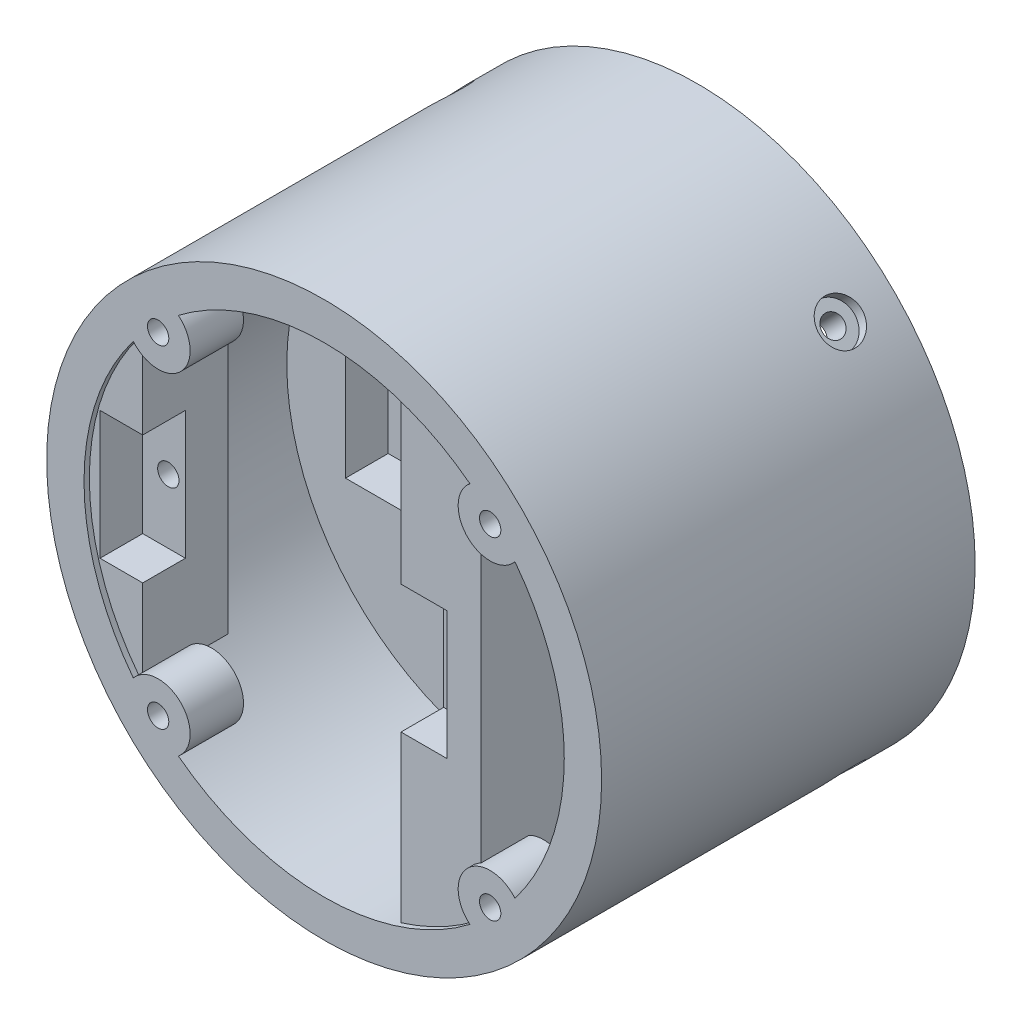
SolidWorks part; units mm, degrees
material "ABS"
ref_plane "Спереди" through (0, 0, 0) normal (0, 0, 1) x (1, 0, 0)
ref_plane "Сверху" through (0, 0, 0) normal (0, 1, 0) x (1, 0, 0)
ref_plane "Справа" through (0, 0, 0) normal (1, 0, 0) x (0, 0, -1)
sketch "Эскиз1" plane through (0, 0, 0) normal (0, 0, 1) x (1, 0, 0)
  circle A1 centre (0, 0) radius 26
  dimension "D1" = 52
extrude "Бобышка-Вытянуть1" add sketch "Эскиз1" along normal blind 35
sketch "Эскиз3" plane through (0, 0, 0) normal (0, 0, -1) x (-1, 0, 0)
  circle A0 centre (0, 0) radius 22.5
  dimension "D1" = 45
extrude "Вырез-Вытянуть1" cut sketch "Эскиз3" against normal blind 11 contours A0
sketch "Эскиз10" plane through (0, 0, 11) normal (0, 0, -1) x (-1, 0, 0)
  circle A0 centre (0, 0) radius 15
  dimension "D1" = 30
sketch "Эскиз4" plane through (0, 0, 35) normal (0, 0, 1) x (1, 0, 0)
  circle A0 centre (0, 0) radius 22.5
  dimension "D1" = 45
extrude "Вырез-Вытянуть2" cut sketch "Эскиз4" against normal offset from surface (19 mm away) 5 up to face at (-22.5, 0, 11)
sketch "Эскиз13" plane through (0, 0, 16) normal (0, 0, 1) x (1, 0, 0)
  line L0 (0, 26) -> (0, -26) construction
  line L1 (-26, 0) -> (26, 0) construction
  line L3 (-17, 6.5) -> (7, 6.5)
  line L4 (-17, 6.5) -> (-17, -6.5)
  line L5 (-17, -6.5) -> (7, -6.5)
  line L6 (7, 6.5) -> (7, -6.5)
  circle A0 centre (0, 0) radius 26 construction
  point P11 (-17, 0)
  point P13 (-5, 6.5)
  dimension "D1" = 13
  dimension "D2" = 24
  dimension "D3" = 5
extrude "Вырез-Вытянуть3" cut sketch "Эскиз13" against normal blind 4
sketch "Эскиз12" plane through (0, 0, 35) normal (0, 0, 1) x (1, 0, 0)
  line L0 (0, 26) -> (0, -26) construction
  line L1 (0, 0) -> (28.1458, 16.25) construction
  line L2 (-26, 0) -> (32.5, 0) construction
  line L5 (19.4856, 11.25) -> (22.5167, 13)
  line L6 (19.4856, -11.25) -> (22.5167, -13)
  circle A0 centre (0, 0) radius 26 construction
  arc A4 (19.4856, -11.25) -> (19.4856, 11.25) centre (0, 0) ccw
  arc A6 (22.5167, -13) -> (22.5167, 13) centre (0, 0) ccw
  dimension "D1" = 30
ref_plane "Плоскость2" through (0, 0, 26.5) normal (0, 0, 1) x (1, 0, 0)
sketch "Эскиз14" plane through (0, 0, 26.5) normal (0, 0, 1) x (1, 0, 0)
  line L1 (7, 0) -> (-46.5151, 0) construction
  line L2 (7, -6.5) -> (7, 6.5) construction
  line L3 (-17.5, -28.5313) -> (-17.5, 17.8536) construction
  line L6 (7, 0) -> (57.6607, 0) construction
  line L8 (14.2, -44.5711) -> (14.2, 20) construction
  line L10 (14.2, -20.5757) -> (14.2, 20.5757)
  line L13 (-17.5, -17.8536) -> (-17.5, 17.8536)
  line L15 (6.7, -24.0855) -> (6.7, 24.0855)
  line L16 (0, -28.5313) -> (0, 28.5313) construction
  arc A4 (-17.5, 17.8536) -> (-17.5, -17.8536) centre (0, 0) ccw
  arc A5 (14.2, 20.5757) -> (6.7, 24.0855) centre (0, 0) ccw
  arc A6 (6.7, -24.0855) -> (14.2, -20.5757) centre (0, 0) ccw
  point P11 (-17.5, 0)
  point P18 (7, 0)
  point P22 (14.2, 0)
  point P27 (14.2, 0)
  point P29 (-17.5, 0)
  point P33 (7.5, 0)
  point P34 (6.7, 0)
  point P35 (0, 0)
  dimension "D1" = 17.5
  dimension "D4" = 6.7
extrude "Бобышка-Вытянуть2" add sketch "Эскиз14" along normal blind 8
sketch "Эскиз15" plane through (0, 0, 34.5) normal (0, 0, 1) x (1, 0, 0)
  line L0 (43.3889, 0) -> (-43.3889, 0) construction
  line L1 (0, 36.1435) -> (0, -36.1435) construction
  line L2 (-21.5, 29.8665) -> (-21.5, -29.8665) construction
  line L3 (11, 32.0712) -> (11, -32.0712) construction
  line L4 (-17.5, 23.7559) -> (-17.5, -23.2484) construction
  line L5 (-21.5, -6) -> (-21.5, 6)
  line L6 (-21.5, 6) -> (-17.5, 6)
  line L7 (6.7, 41.39) -> (6.7, -19.4927) construction
  line L8 (6.7, 21.4793) -> (6.7, -21.4793) construction
  line L9 (11, -6) -> (11, 6)
  line L10 (11, 6) -> (6.7, 6)
  line L11 (-17.5, 6) -> (-17.5, -6)
  line L12 (6.7, 6) -> (6.7, -6)
  line L13 (11, -6) -> (6.7, -6)
  line L14 (-21.5, -6) -> (-17.5, -6)
  point P4 (0, 0)
  point P8 (0, 0)
  point P11 (-21.5, 0)
  point P14 (11, 0)
  point P19 (-17.5, 0.2537)
  point P24 (6.7, 10.9487)
  point P30 (6.7, 0)
  point P31 (11, 0)
  point P32 (-17.5, 0)
  point P33 (-21.5, 0)
  dimension "D1" = 21.5
  dimension "D2" = 11
  dimension "D3" = 6
  dimension "D4" = 6
extrude "Вырез-Вытянуть5" cut sketch "Эскиз15" along direction (0, 0, 1) on the side against the normal offset from surface (4 mm away) 18.5
sketch "Эскиз17" plane through (0, 0, 30.5) normal (0, 0, 1) x (1, 0, 0)
  circle A1 centre (-19.1, 0) radius 1
  circle A2 centre (8.6, 0) radius 1
extrude "Вырез-Вытянуть6" cut sketch "Эскиз17" along direction (0, 0, 1) on the side against the normal up to surface (4 mm away)
sketch "Эскиз20" plane through (0, 0, 35) normal (0, 0, 1) x (1, 0, 0)
  line L0 (-57.2124, 0) -> (57.2124, 0) construction
  line L1 (0, 34.3681) -> (0, -34.3681) construction
  line L2 (0, 0) -> (-44.2288, 44.2288) construction
  circle A0 centre (0, 0) radius 22 construction
  circle A2 centre (0, 0) radius 26 construction
  circle A3 centre (-15.5563, 15.5563) radius 3
  circle A4 centre (15.5563, 15.5563) radius 3
  circle A5 centre (15.5563, -15.5563) radius 3
  circle A6 centre (-15.5563, -15.5563) radius 3
  point P3 (-15.5563, 15.5563)
  point P8 (0, 0)
  point P12 (0, 0)
  point P23 (0, 0)
  point P27 (0, 0)
  dimension "D2" = 52
  dimension "D3" = 22
  dimension "D1" = 6
  dimension "D4" = 4
extrude "Бобышка-Вытянуть3" add sketch "Эскиз20" against normal blind 5
sketch "Эскиз21" plane through (0, 0, 35) normal (0, 0, 1) x (1, 0, 0)
  circle A4 centre (-15.5563, 15.5563) radius 1
  circle A11 centre (15.5563, 15.5563) radius 1
  circle A12 centre (15.5563, -15.5563) radius 1
  circle A13 centre (-15.5563, -15.5563) radius 1
  point P11 (-0.7071, 0)
  point P12 (0, 0)
  point P14 (0.7071, 0)
  point P15 (0, 0)
  dimension "D1" = 2
  dimension "D2" = 4
extrude "Вырез-Вытянуть9" cut sketch "Эскиз21" against normal blind 5
sketch "Эскиз24" plane through (0, 0, 16) normal (0, 0, 1) x (1, 0, 0)
  line L0 (7, -6.5) -> (7, 6.5) construction
  line L1 (11, 4) -> (13.5, 4)
  line L2 (11, 4) -> (11, -4)
  line L3 (11, -4) -> (13.5, -4)
  line L4 (13.5, 4) -> (13.5, -4)
  point P7 (11, 0)
  point P10 (7, 0)
  dimension "D1" = 2.5
  dimension "D2" = 8
  dimension "D4" = 4
extrude "Вырез-Вытянуть12" cut sketch "Эскиз24" against normal up to surface (5 mm away) up to face at (-22.5, 0, 11)
ref_plane "Плоскость3" through (-18.3848, -18.3848, 35) normal (-0.7071, -0.7071, 0) x (-0.7071, 0.7071, 0)
sketch "Эскиз25" plane through (-18.3848, -18.3848, 35) normal (-0.7071, -0.7071, 0) x (-0.7071, 0.7071, 0)
  line L0 (0, 0) -> (0, 35) construction
  circle A0 centre (0, 30) radius 2
  dimension "D1" = 4
  dimension "D2" = 5
extrude "Вырез-Вытянуть13" cut sketch "Эскиз25" against normal blind 1
sketch "Эскиз26" plane through (-17.6777, -17.6777, 0) normal (-0.7071, -0.7071, 0) x (0, 0, 1)
  circle A0 centre (5, 0) radius 1
  dimension "D1" = 2
extrude "Вырез-Вытянуть14" cut sketch "Эскиз26" against normal through all
pattern_circular "Круговой массив1" count 4 over 360 about axis through (0, 0, 0) along (0, 0, 1) of "Вырез-Вытянуть14", "Вырез-Вытянуть13"
chamfer "Фаска1" distance 0.5 angle 45 1 edges at (-22.5, 0, 0)
